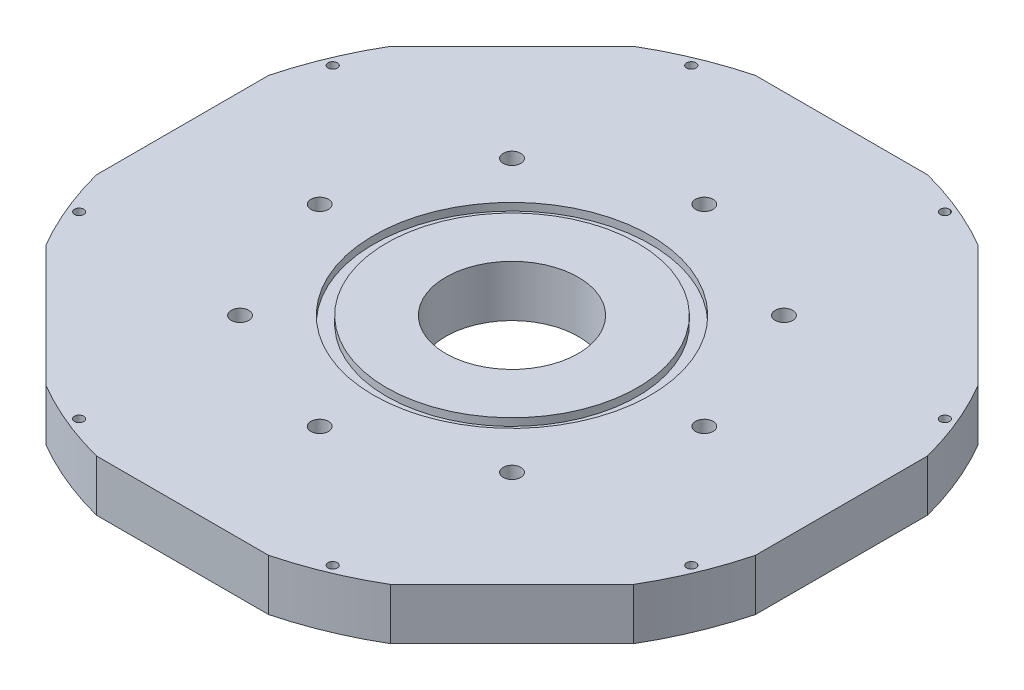
SolidWorks part; units mm, degrees
material "6061-T4 (SS)"
ref_plane "Front Plane" through (0, 0, 0) normal (0, 0, 1) x (1, 0, 0)
ref_plane "Top Plane" through (0, 0, 0) normal (0, 1, 0) x (1, 0, 0)
ref_plane "Right Plane" through (0, 0, 0) normal (1, 0, 0) x (0, 0, -1)
sketch "Sketch1" plane through (0, 0, 0) normal (0, 1, 0) x (1, 0, 0)
  line L1 (-50.6583, 122.3) -> (-122.3, 50.6583)
  line L2 (-122.3, 50.6583) -> (-122.3, -50.6583)
  line L3 (-122.3, -50.6583) -> (-50.6583, -122.3)
  line L4 (-50.6583, -122.3) -> (50.6583, -122.3)
  line L5 (50.6583, -122.3) -> (122.3, -50.6583)
  line L6 (122.3, -50.6583) -> (122.3, 50.6583)
  line L7 (122.3, 50.6583) -> (50.6583, 122.3)
  line L8 (50.6583, 122.3) -> (-50.6583, 122.3)
  circle A0 centre (0, 0) radius 122.3 construction
  circle A1 centre (0, 0) radius 126.4
  dimension "D2" = 252.8
  dimension "D1" = 244.6
extrude "Boss-Extrude1" add sketch "Sketch1" along normal blind 19.05 contours L4 A1 L5 L6 L7 L8 L1 L2 L3
sketch "Sketch3" plane through (0, 19.05, 0) normal (0, 1, 0) x (1, 0, 0)
  circle A0 centre (0, 0) radius 24.5745
  dimension "D1" = 49.149
extrude "Cut-Extrude1" cut sketch "Sketch3" against normal through all contours A0
sketch "Sketch5" plane through (0, 19.05, 0) normal (0, 1, 0) x (1, 0, 0)
  circle A0 centre (0, 0) radius 46.5455
  circle A1 centre (0, 0) radius 51.3715
  dimension "D1" = 93.091
  dimension "D2" = 102.743
extrude "Cut-Extrude2" cut sketch "Sketch5" against normal blind 2.794
sketch "Sketch19" plane through (0, 19.05, 0) normal (0, 1, 0) x (1, 0, 0)
  line L0 (-115.3833, 47.7933) -> (-116.7784, 48.3712)
  line L1 (-119.5501, 41.6796) -> (-111.6676, 60.7097) construction
  line L2 (-116.9739, 43.9532) -> (-114.6894, 49.4685) construction
  line L3 (-122.3, 31.9323) -> (-109.0587, 63.8996) construction
  line L5 (-63.8996, 109.0587) -> (-31.9323, 122.3) construction
  line L6 (-47.916, 115.6793) -> (-43.6974, 105.4949) construction
  circle A0 centre (-113.7876, 47.1324) radius 1.7272
  arc A1 (-109.0587, 63.8996) -> (-122.3, 31.9323) centre (0, 0) ccw construction
  arc A2 (-109.0587, 63.8996) -> (-122.3, 31.9323) centre (0, 0) ccw
  circle A4 centre (0, 0) radius 122.9618
  circle A5 centre (-47.0555, 113.6019) radius 1.7272
  point P9 (-115.6793, 47.916)
  point P10 (-115.3833, 47.7933)
  dimension "D1" = 3.4544
  dimension "D3" = 245.9237
  dimension "D4" = 3.4544
  dimension "D2" = 1.51
extrude "Cut-Extrude4" cut sketch "Sketch19" against normal through all contours A4 A5 | A4 A5 | A0
pattern_circular "CirPattern2" count 8 over 360 about axis through (0, 0, 0) along (0, 1, 0) of "Cut-Extrude4"
sketch "Sketch21" plane through (0, 19.05, 0) normal (0, 1, 0) x (1, 0, 0)
  point P0 (-71.374, 0)
  dimension "D1" = 71.374
hole_wizard "5/16-18 Tapped Hole2" positions "Sketch22" profile "Sketch23" tap size "5/16-18" standard "ANSI Inch"
sketch "Sketch22" plane through (0, 19.05, 0) normal (0, 1, 0) x (1, 0, 0)
  point P0 (-71.374, 0)
sketch "Sketch23" plane through (-71.374, 19.05, 0) normal (1, 0, 0) x (0, 0, 1)
  line L0 (0, 0) -> (0, 14.6611)
  line L1 (0, 14.6611) -> (3.2639, 12.7)
  line L2 (3.2639, 12.7) -> (3.2639, 0)
  line L5 (3.2639, 0) -> (0, 0)
  line L10 (0, 14.6611) -> (-3.2639, 12.7) construction
  line L11 (0, -6.35) -> (0, 107.95) construction
  dimension "Tap Drill Dia." = 6.5278
  dimension "Tap Drill Depth" = 12.7
  dimension "Drill Angle" = 118
cosmetic thread "Hole Thread2" parameters "D1"=12.7, "D2"=7.9375
sketch "Sketch33" [suppressed] plane through (0, 19.05, 0) normal (0, 1, 0) x (1, 0, 0)
  circle A0 centre (-71.374, 0) radius 3.9687
  dimension "D1" = 7.9375
sketch "Sketch37" plane through (0, 0, 0) normal (0, -1, 0) x (1, 0, 0)
  circle A0 centre (0, 0) radius 119.0625
  circle A1 centre (0, 0) radius 115.2525
  dimension "D1" = 238.125
  dimension "D2" = 230.505
extrude "Cut-Extrude7" cut sketch "Sketch37" against normal blind 2.667
pattern_circular "CirPattern4" count 8 over 360 about axis through (0, 0, 0) along (0, 1, 0) of "5/16-18 Tapped Hole2"
cosmetic thread "Hole Thread3" parameters "D1"=12.7, "D2"=7.9375
cosmetic thread "Hole Thread4" parameters "D1"=12.7, "D2"=7.9375
cosmetic thread "Hole Thread5" parameters "D1"=12.7, "D2"=7.9375
cosmetic thread "Hole Thread6" parameters "D1"=12.7, "D2"=7.9375
cosmetic thread "Hole Thread7" parameters "D1"=12.7, "D2"=7.9375
cosmetic thread "Hole Thread8" parameters "D1"=12.7, "D2"=7.9375
cosmetic thread "Hole Thread9" parameters "D1"=12.7, "D2"=7.9375
